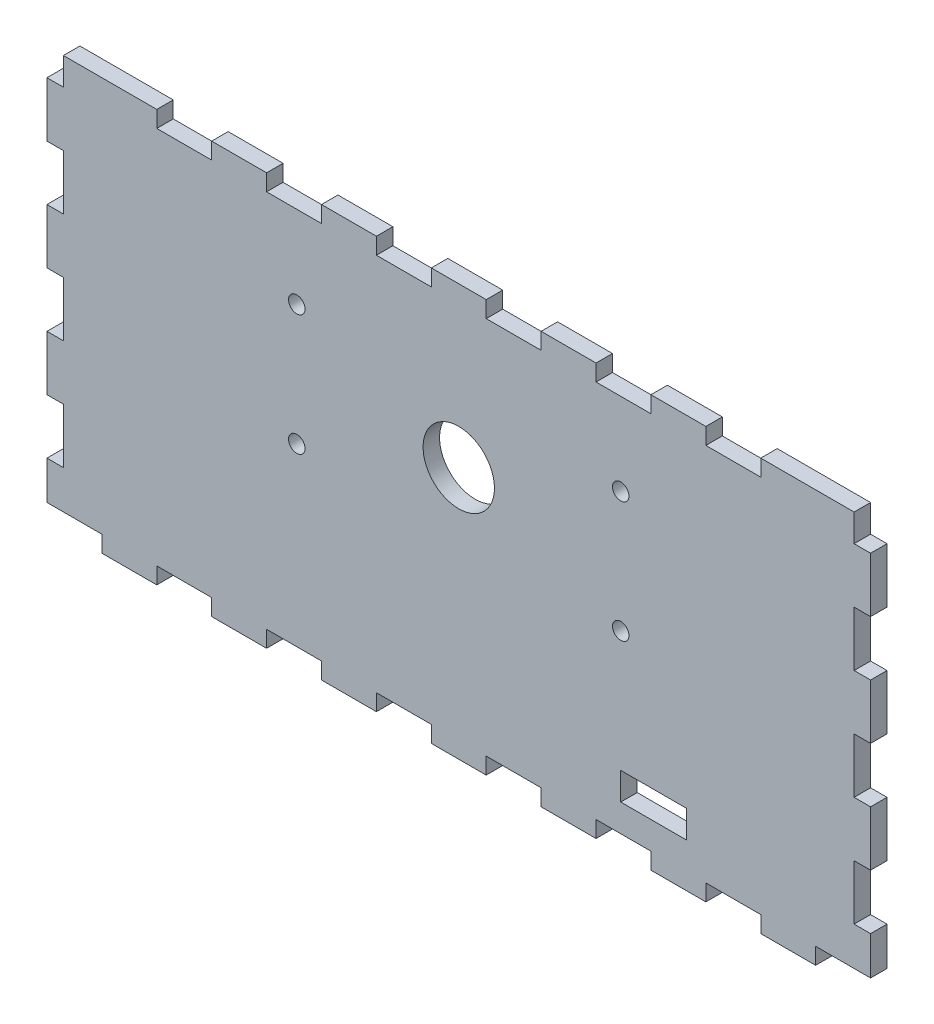
SolidWorks part; units mm, degrees
ref_plane "Plano frontal" through (0, 0, 0) normal (0, 0, 1) x (1, 0, 0)
ref_plane "Plano superior" through (0, 0, 0) normal (0, 1, 0) x (1, 0, 0)
ref_plane "Plano direito" through (0, 0, 0) normal (1, 0, 0) x (0, 0, -1)
sketch "mdfEsb" plane through (0, 0, 0) normal (0, 0, 1) x (1, 0, 0)
  line L1 (0, 75) -> (150, 75)
  line L2 (0, 75) -> (0, 0)
  line L3 (0, 0) -> (150, 0)
  line L4 (150, 75) -> (150, 0)
  dimension "D1" = 150
  dimension "D2" = 75
extrude "mdf" add sketch "mdfEsb" along normal blind 3
sketch "EncaixesEsb" plane through (0, 0, 3) normal (0, 0, 1) x (1, 0, 0)
  line L0 (20, 0) -> (20, 3)
  line L1 (0, 0) -> (10, 0)
  line L2 (0, 0) -> (0, 3)
  line L3 (0, 3) -> (10, 3)
  line L4 (10, 0) -> (10, 3)
  line L5 (20, 0) -> (30, 0)
  line L6 (30, 0) -> (30, 3)
  line L7 (20, 3) -> (30, 3)
  line L8 (40, 0) -> (40, 3)
  line L9 (40, 0) -> (50, 0)
  line L10 (50, 0) -> (50, 3)
  line L11 (40, 3) -> (50, 3)
  line L12 (60, 0) -> (60, 3)
  line L13 (60, 0) -> (70, 0)
  line L14 (70, 0) -> (70, 3)
  line L15 (60, 3) -> (70, 3)
  line L16 (80, 0) -> (80, 3)
  line L17 (80, 0) -> (90, 0)
  line L18 (90, 0) -> (90, 3)
  line L19 (80, 3) -> (90, 3)
  line L20 (100, 0) -> (100, 3)
  line L21 (100, 0) -> (110, 0)
  line L22 (110, 0) -> (110, 3)
  line L23 (100, 3) -> (110, 3)
  line L24 (120, 0) -> (120, 3)
  line L25 (120, 0) -> (130, 0)
  line L26 (130, 0) -> (130, 3)
  line L27 (120, 3) -> (130, 3)
  line L28 (140, 0) -> (140, 3)
  line L29 (140, 0) -> (150, 0)
  line L30 (150, 0) -> (150, 3)
  line L31 (140, 3) -> (150, 3)
  line L32 (0, 75) -> (0, 0) construction
  line L33 (0, 10) -> (3, 10)
  line L34 (0, 10) -> (0, 20)
  line L35 (0, 20) -> (3, 20)
  line L36 (3, 10) -> (3, 20)
  line L37 (147, 10) -> (147, 20)
  line L38 (147, 10) -> (150, 10)
  line L39 (150, 10) -> (150, 20)
  line L40 (147, 20) -> (150, 20)
  line L41 (147, 30) -> (147, 40)
  line L42 (147, 30) -> (150, 30)
  line L43 (150, 30) -> (150, 40)
  line L44 (147, 40) -> (150, 40)
  line L45 (147, 50) -> (147, 60)
  line L46 (147, 50) -> (150, 50)
  line L47 (150, 50) -> (150, 60)
  line L48 (147, 60) -> (150, 60)
  line L49 (147, 70) -> (147, 80)
  line L50 (147, 70) -> (150, 70)
  line L51 (150, 70) -> (150, 80)
  line L52 (147, 80) -> (150, 80)
  line L57 (0, 30) -> (0, 40)
  line L58 (0, 30) -> (3, 30)
  line L59 (3, 30) -> (3, 40)
  line L60 (0, 40) -> (3, 40)
  line L61 (0, 50) -> (0, 60)
  line L62 (0, 50) -> (3, 50)
  line L63 (3, 50) -> (3, 60)
  line L64 (0, 60) -> (3, 60)
  line L65 (0, 70) -> (0, 80)
  line L66 (0, 70) -> (3, 70)
  line L67 (3, 70) -> (3, 80)
  line L68 (0, 80) -> (3, 80)
  line L73 (0, 10) -> (147, 10) construction
  line L74 (0, 10) -> (0, 30) construction
  line L75 (150, 0) -> (150, 75) construction
  line L76 (20, 72) -> (20, 75)
  line L77 (20, 72) -> (30, 72)
  line L78 (30, 72) -> (30, 75)
  line L79 (20, 75) -> (30, 75)
  line L80 (40, 72) -> (40, 75)
  line L81 (40, 72) -> (50, 72)
  line L82 (50, 72) -> (50, 75)
  line L83 (40, 75) -> (50, 75)
  line L84 (60, 72) -> (60, 75)
  line L85 (60, 72) -> (70, 72)
  line L86 (70, 72) -> (70, 75)
  line L87 (60, 75) -> (70, 75)
  line L88 (80, 72) -> (80, 75)
  line L89 (80, 72) -> (90, 72)
  line L90 (90, 72) -> (90, 75)
  line L91 (80, 75) -> (90, 75)
  line L92 (100, 72) -> (100, 75)
  line L93 (100, 72) -> (110, 72)
  line L94 (110, 72) -> (110, 75)
  line L95 (100, 75) -> (110, 75)
  line L96 (120, 72) -> (120, 75)
  line L97 (120, 72) -> (130, 72)
  line L98 (130, 72) -> (130, 75)
  line L99 (120, 75) -> (130, 75)
  line L100 (150, 75) -> (0, 75) construction
  line L101 (0, 90) -> (0, 100) [skipped]
  line L102 (0, 100) -> (3, 100) [skipped]
  line L103 (3, 90) -> (3, 100) [skipped]
  line L104 (0, 90) -> (3, 90) [skipped]
  line L105 (147, 90) -> (147, 100) [skipped]
  line L106 (147, 100) -> (150, 100) [skipped]
  line L107 (150, 90) -> (150, 100) [skipped]
  line L108 (147, 90) -> (150, 90) [skipped]
  point P39 (5, 0)
  dimension "D1" = 10
  dimension "D2" = 3
  dimension "D4" = 10
  dimension "D5" = 3
  dimension "D6" = 10
  dimension "D7" = 90
  dimension "D8" = 20
  dimension "D11" = 10
  dimension "D3" = 8
  dimension "D9" = 2
  dimension "D10" = 5
  dimension "D12" = 2
extrude "Encaixes" cut sketch "EncaixesEsb" against normal blind 3
sketch "motorPassoEsb" plane through (0, 0, 3) normal (0, 0, 1) x (1, 0, 0)
  line L0 (45.5, 35) -> (104.5, 35) construction
  line L1 (45.5, 35) -> (45.5, 57) construction
  line L2 (75, 0) -> (75, 75) construction
  line L3 (70, 0) -> (80, 0) construction
  line L4 (80, 75) -> (70, 75) construction
  line L6 (104.5, 13) -> (116.5, 13)
  line L7 (104.5, 13) -> (104.5, 8)
  line L8 (104.5, 8) -> (116.5, 8)
  line L9 (116.5, 13) -> (116.5, 8)
  circle A4 centre (45.5, 35) radius 1.5
  circle A5 centre (104.5, 35) radius 1.5
  circle A6 centre (104.5, 57) radius 1.5
  circle A7 centre (45.5, 57) radius 1.5
  circle A8 centre (75, 46) radius 6.5
  point P10 (45.5, 46)
  dimension "D3" = 3
  dimension "D2" = 13
  dimension "D1" = 29.5
  dimension "D4" = 90
  dimension "D5" = 59
  dimension "D6" = 22
  dimension "D7" = 35
  dimension "D8" = 22
  dimension "D9" = 12
  dimension "D10" = 5
extrude "motorPasso" cut sketch "motorPassoEsb" against normal blind 3
